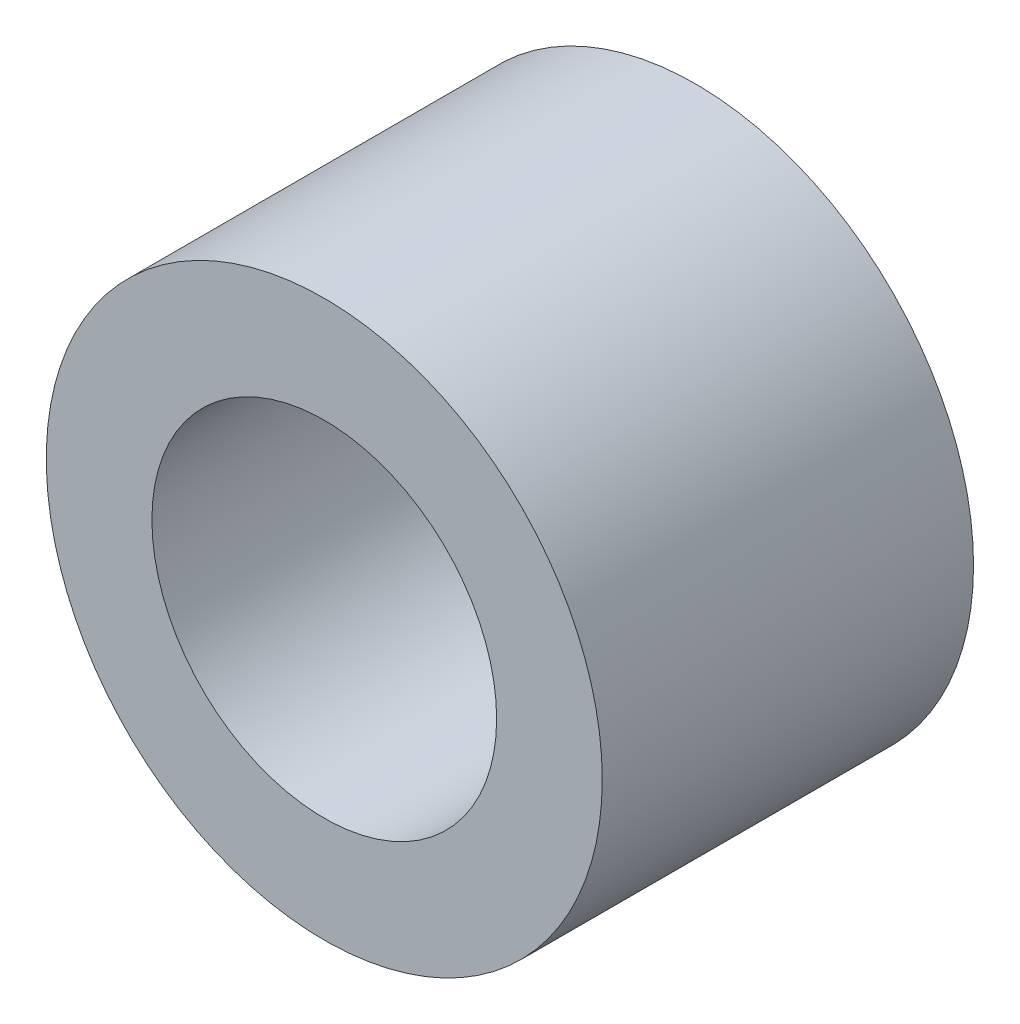
SolidWorks part; units mm, degrees
ref_plane "Front Plane" through (0, 0, 0) normal (0, 0, 1) x (1, 0, 0)
ref_plane "Top Plane" through (0, 0, 0) normal (0, 1, 0) x (1, 0, 0)
ref_plane "Right Plane" through (0, 0, 0) normal (1, 0, 0) x (0, 0, -1)
sketch "Sketch1" plane through (0, 0, 0) normal (0, 0, 1) x (1, 0, 0)
  circle A0 centre (0, 0) radius 20.1586
  circle A1 centre (0, 0) radius 12.5
  dimension "D1" = 25
  dimension "D2" = 40.3173
extrude "Boss-Extrude1" add sketch "Sketch1" along normal blind 26.924
